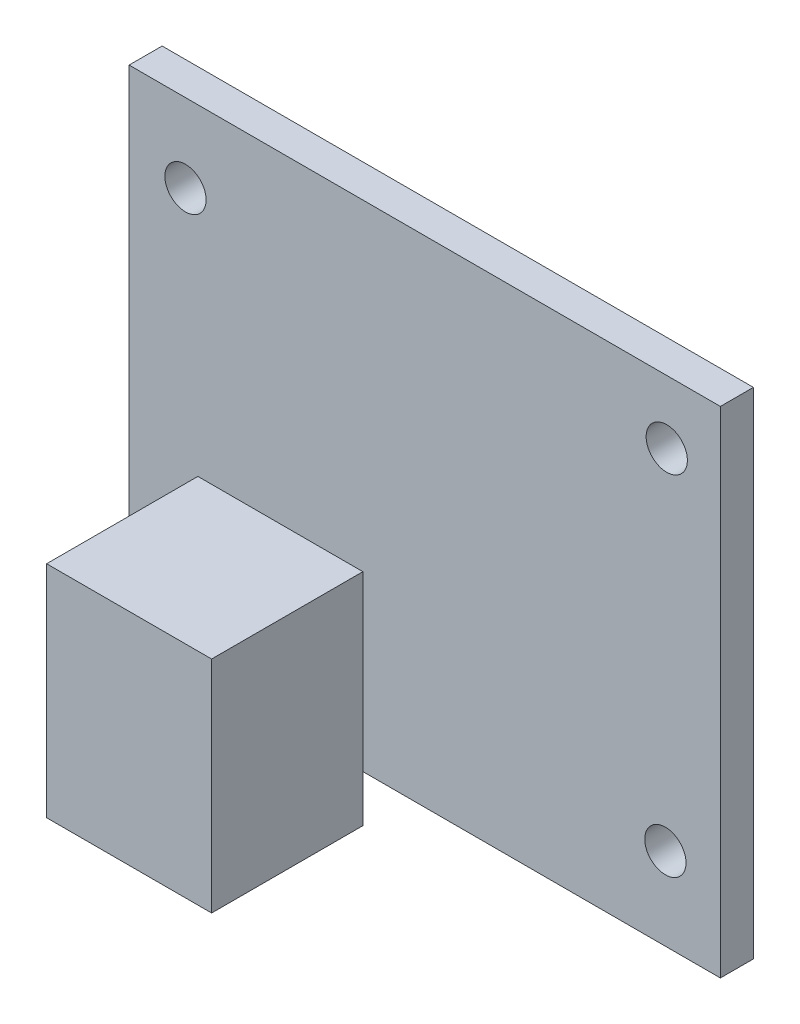
SolidWorks part; units mm, degrees
ref_plane "Front Plane" through (0, 0, 0) normal (0, 0, 1) x (1, 0, 0)
ref_plane "Top Plane" through (0, 0, 0) normal (0, 1, 0) x (1, 0, 0)
ref_plane "Right Plane" through (0, 0, 0) normal (1, 0, 0) x (0, 0, -1)
sketch "Sketch1" plane through (0, 0, 0) normal (0, 0, 1) x (1, 0, 0)
  line L1 (0, 0) -> (43, 0)
  line L2 (0, 0) -> (0, 36)
  line L3 (0, 36) -> (43, 36)
  line L4 (43, 0) -> (43, 36)
  circle A0 centre (39, 6) radius 1.5
  circle A1 centre (4.1, 30.3) radius 1.5
  circle A2 centre (39.1, 31.4) radius 1.5
  point P11 (5.5876, 31.8249)
  point P12 (5.4256, 29.5574)
  dimension "D9" = 3
  dimension "D1" = 43
  dimension "D2" = 36
  dimension "D3" = 4
  dimension "D4" = 6
  dimension "D5" = 3.9
  dimension "D6" = 25.4
  dimension "D7" = 5.7
  dimension "D8" = 35
extrude "Boss-Extrude1" add sketch "Sketch1" along normal blind 2.4
sketch "Sketch2" plane through (0, 0, 2.4) normal (0, 0, 1) x (1, 0, 0)
  line L0 (0, 36) -> (0, 0) construction
  line L1 (5, 12.5919) -> (17, 12.5919)
  line L2 (5, 12.5919) -> (5, -3.4081)
  line L3 (5, -3.4081) -> (17, -3.4081)
  line L4 (17, 12.5919) -> (17, -3.4081)
  dimension "D1" = 12
  dimension "D2" = 16
  dimension "D3" = 5
extrude "Boss-Extrude2" add sketch "Sketch2" along normal blind 11
